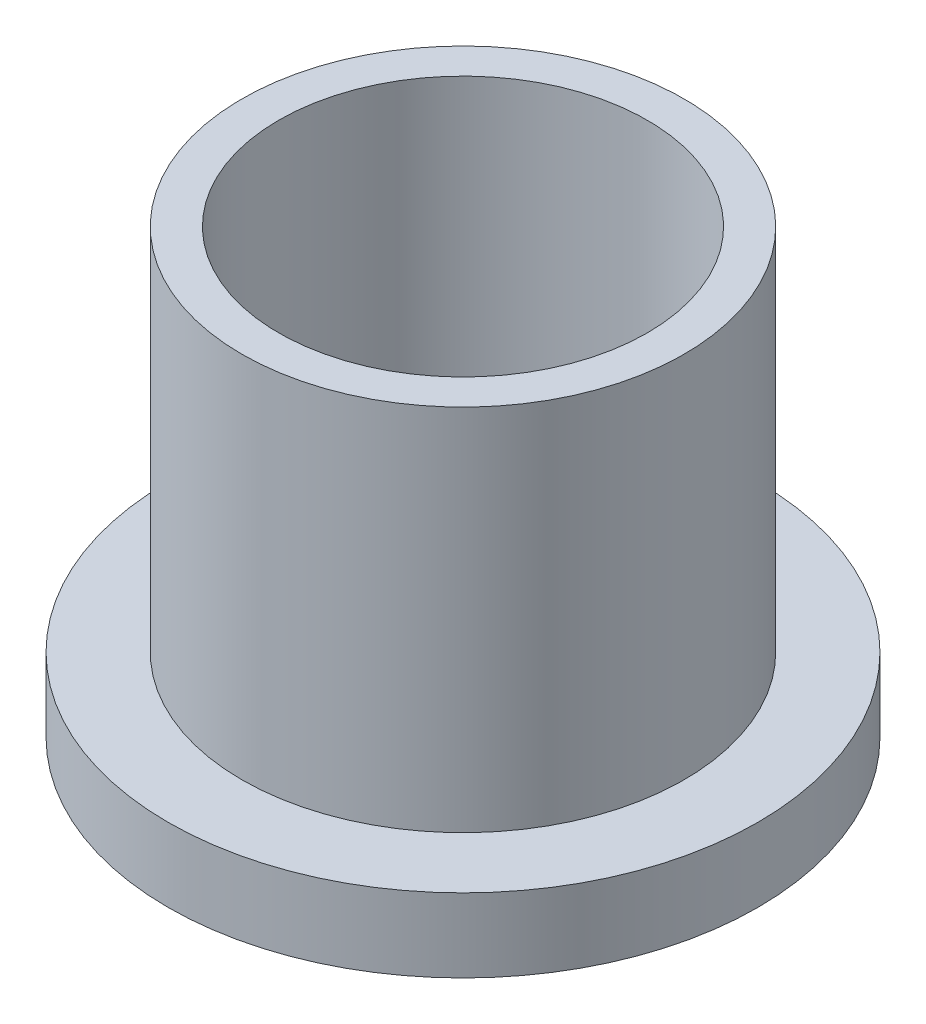
SolidWorks part; units mm, degrees
ref_plane "Plan de face" through (0, 0, 0) normal (0, 0, 1) x (1, 0, 0)
ref_plane "Plan de dessus" through (0, 0, 0) normal (0, 1, 0) x (1, 0, 0)
ref_plane "Plan de droite" through (0, 0, 0) normal (1, 0, 0) x (0, 0, -1)
sketch "Esquisse1" plane through (0, 0, 0) normal (0, 1, 0) x (1, 0, 0)
  circle A0 centre (0, 0) radius 6
  dimension "D1" = 12
extrude "Cylindre" add sketch "Esquisse1" along normal blind 10 thin thin type one direction reverse wall 1
sketch "Esquisse2" plane through (0, 0, 0) normal (0, -1, 0) x (1, 0, 0)
  circle A0 centre (0, 0) radius 8
  dimension "D1" = 16
extrude "Base" add sketch "Esquisse2" along normal blind 2
